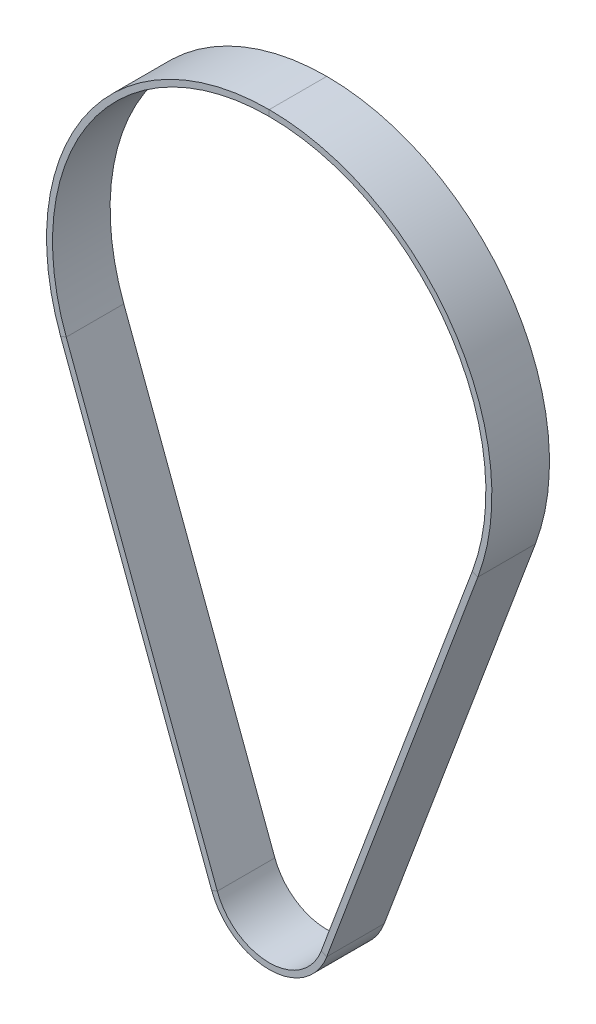
SolidWorks part; units mm, degrees
ref_plane "Спереди" through (0, 0, 0) normal (0, 0, 1) x (1, 0, 0)
ref_plane "Сверху" through (0, 0, 0) normal (0, 1, 0) x (1, 0, 0)
ref_plane "Справа" through (0, 0, 0) normal (1, 0, 0) x (0, 0, -1)
other "Configuration Table"
sketch "Эскиз1" plane through (0, 0, 0) normal (0, 0, 1) x (1, 0, 0)
  line L0 (-54.3315, -20.3) -> (-14.988, -125.6)
  line L2 (14.988, -125.6) -> (54.3315, -20.3)
  arc A0 (54.3315, -20.3) -> (-54.3315, -20.3) centre (0, 0) ccw
  arc A1 (-14.988, -125.6) -> (14.988, -125.6) centre (0, -120) ccw
  dimension "D1" = 116
  dimension "D2" = 32
  dimension "D3" = 120
sketch "Эскиз2" plane through (0, 0, 0) normal (1, 0, 0) x (0, 0, -1)
  line L0 (0, 58) -> (0, -20.3) construction
  line L1 (-15, 58) -> (0, 58)
  line L2 (-15, 58) -> (-15, 56.44)
  line L3 (-15, 56.44) -> (0, 56.44)
  line L4 (0, 58) -> (0, 56.44)
  dimension "D1" = 1.56
  dimension "D2" = 15
  dimension "D3" = 58
sweep "По траектории1" add profiles "Эскиз2" path "Эскиз1"
